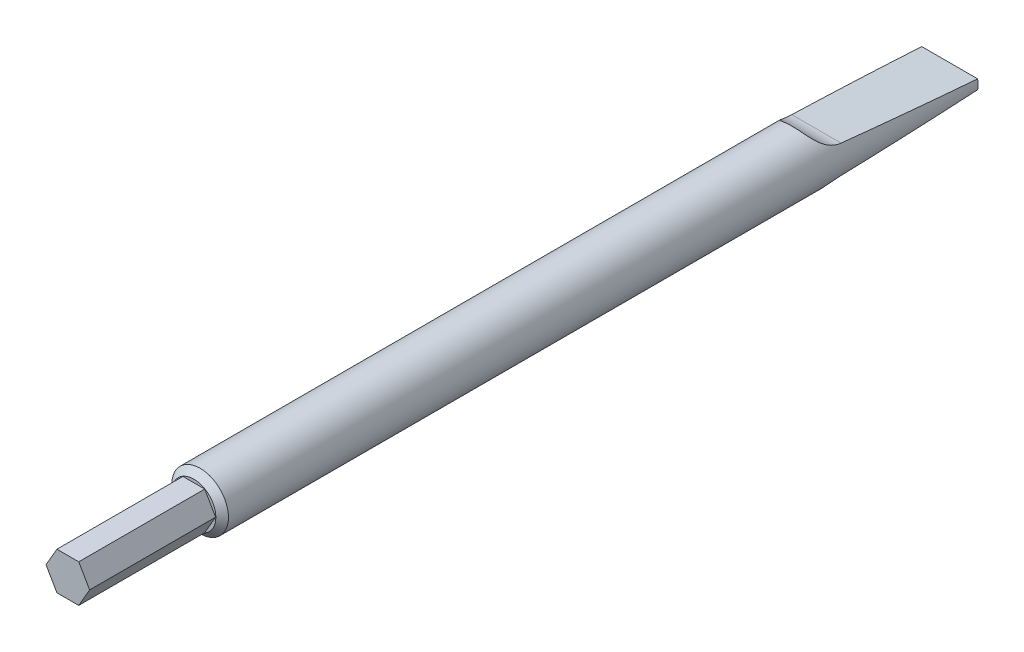
SolidWorks part; units mm, degrees
ref_plane "Front Plane" through (0, 0, 0) normal (1, 0, 0) x (0, 1, 0)
ref_plane "Top Plane" through (0, 0, 0) normal (0, 0, 1) x (0, 1, 0)
ref_plane "Right Plane" through (0, 0, 0) normal (0, 1, 0) x (-1, 0, 0)
sketch "Sketch2" plane through (0, 0, 0) normal (0, 0, 1) x (0, 1, 0)
  circle A0 centre (0, 0) radius 4.5
  dimension "D1" = 9
extrude "Boss-Extrude1" add sketch "Sketch2" along normal blind 140
sketch "Sketch3" plane through (0, 0, 0) normal (1, 0, 0) x (0, 1, 0)
  line L1 (-4.5, 140) -> (-4.5, 0) construction
  line L2 (-2.229, 21.1513) -> (-0.75, 0)
  line L3 (-4.5, 0) -> (4.5, 0) construction
  line L4 (0, -4.95) -> (0, 4.95) construction
  line L5 (2.229, 21.1513) -> (0.75, 0)
  line L6 (-0.75, 0) -> (0.75, 0) construction
  line L7 (0, 0) -> (0, 12.0451) construction
  line L8 (4.5, 0) -> (4.5, 140) construction
  line L9 (4.5, 25) -> (4.5, 0)
  line L10 (4.5, 0) -> (0.75, 0)
  line L11 (-4.5, 25) -> (-4.5, 0)
  line L12 (-4.5, 0) -> (-0.75, 0)
  arc A0 (-4.5, 25) -> (-2.229, 21.1513) centre (-7.2169, 20.8025) cw
  arc A1 (4.5, 25) -> (2.229, 21.1513) centre (7.2169, 20.8025) ccw
  dimension "D2" = 5
  dimension "D1" = 4
  dimension "D3" = 25
  dimension "D4" = 1.5
extrude "Cut-Extrude1" cut sketch "Sketch3" against normal mid plane 9
sketch "Sketch4" plane through (0, 0, 0) normal (0, 0, 1) x (0, 1, 0)
  line L0 (0, 0) -> (0, 4.7099) construction
  line L8 (-3, 1.7321) -> (-3, -1.7321)
  line L9 (-3, -1.7321) -> (0, -3.4641)
  line L10 (0, -3.4641) -> (3, -1.7321)
  line L11 (3, -1.7321) -> (3, 1.7321)
  line L12 (3, 1.7321) -> (0, 3.4641)
  line L13 (0, 3.4641) -> (-3, 1.7321)
  circle A0 centre (0, 0) radius 3.4641 construction
  circle A1 centre (0, 0) radius 4.5
  dimension "D2" = 9
  dimension "D3" = 6.9282
  dimension "D1" = 6
extrude "Cut-Extrude3" cut sketch "Sketch4" against normal blind 20 from surface at 140 starting at face at (4.5, 0, 140)
chamfer "Chamfer2" distance 1 angle 45 1 edges at (4.5, 0, 120)
